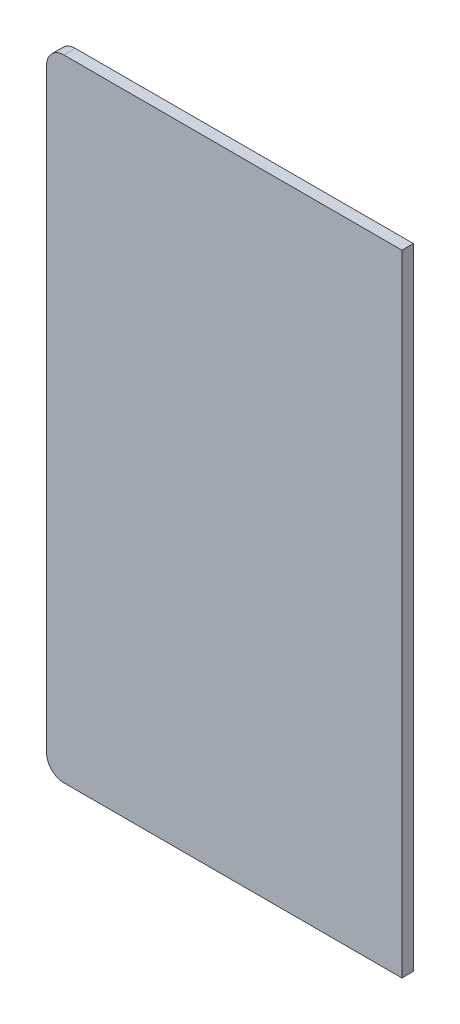
SolidWorks part; units mm, degrees
material "Glass"
ref_plane "Front Plane" through (0, 0, 0) normal (0, 0, 1) x (1, 0, 0)
ref_plane "Top Plane" through (0, 0, 0) normal (0, 1, 0) x (1, 0, 0)
ref_plane "Right Plane" through (0, 0, 0) normal (1, 0, 0) x (0, 0, -1)
sketch "Sketch1" plane through (0, 0, 0) normal (0, 0, 1) x (1, 0, 0)
  line L0 (63.5, 1422.4) -> (63.5, 101.6)
  line L1 (101.6, 63.5) -> (850.9, 63.5)
  line L2 (850.9, 63.5) -> (850.9, 1460.5)
  line L3 (850.9, 1460.5) -> (101.6, 1460.5)
  arc A0 (63.5, 101.6) -> (101.6, 63.5) centre (101.6, 101.6) ccw
  arc A1 (101.6, 1460.5) -> (63.5, 1422.4) centre (101.6, 1422.4) ccw
extrude "Boss-Extrude1" add sketch "Sketch1" along normal blind 25.4 contours L3 A1 L0 A0 L1 L2
